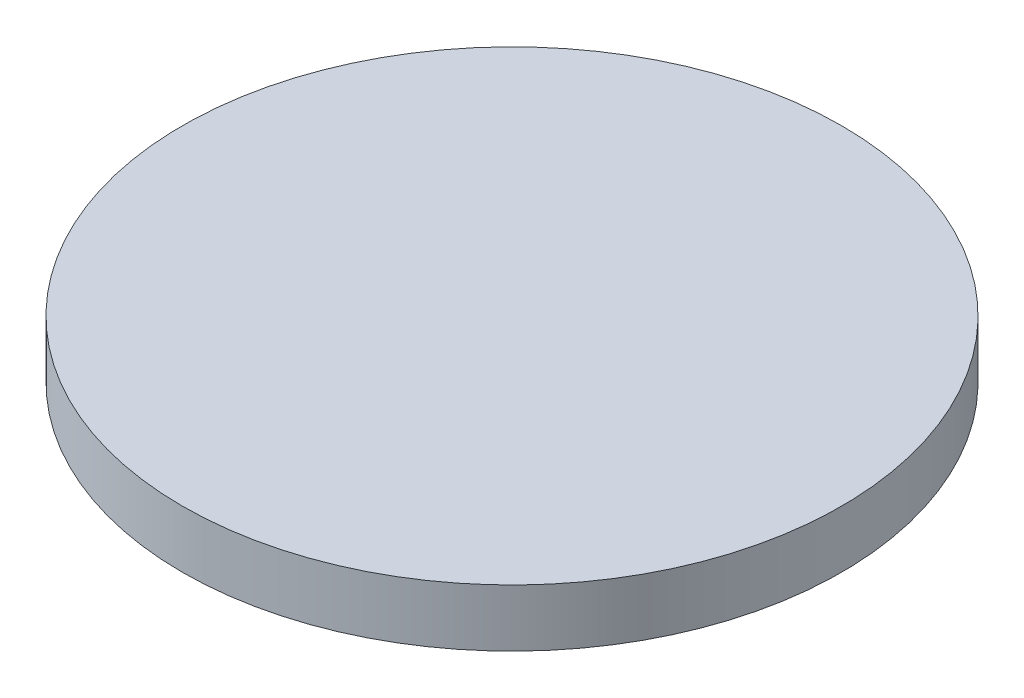
SolidWorks part; units mm, degrees
material "Сосна"
ref_plane "Спереди" through (0, 0, 0) normal (0, 0, 1) x (1, 0, 0)
ref_plane "Сверху" through (0, 0, 0) normal (0, 1, 0) x (1, 0, 0)
ref_plane "Справа" through (0, 0, 0) normal (1, 0, 0) x (0, 0, -1)
sketch "Эскиз1" plane through (0, 0, 0) normal (0, 1, 0) x (1, 0, 0)
  circle A0 centre (0, 0) radius 23
  dimension "D1" = 46
extrude "Бобышка-Вытянуть1" add sketch "Эскиз1" along normal blind 4
